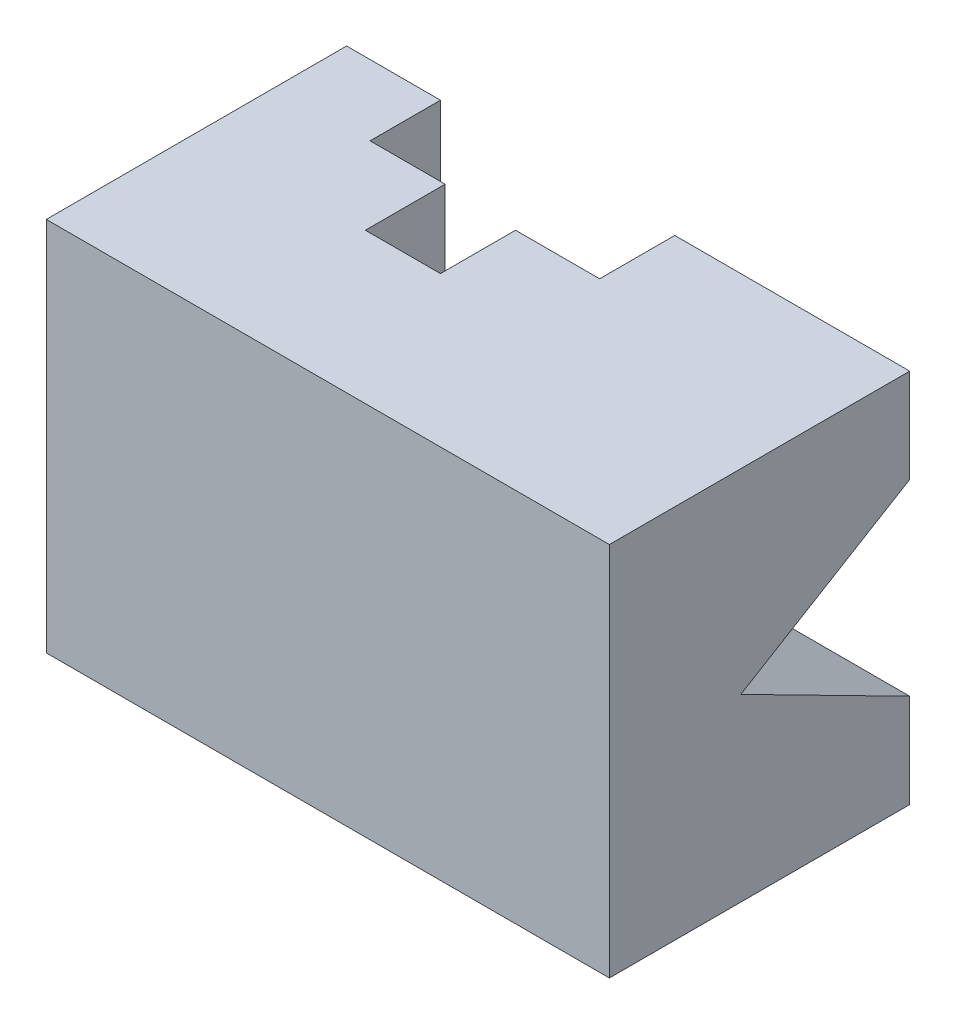
SolidWorks part; units mm, degrees
ref_plane "Front Plane" through (0, 0, 0) normal (0, 0, 1) x (1, 0, 0)
ref_plane "Top Plane" through (0, 0, 0) normal (0, 1, 0) x (1, 0, 0)
ref_plane "Right Plane" through (0, 0, 0) normal (1, 0, 0) x (0, 0, -1)
sketch "Sketch1" plane through (0, 0, 0) normal (0, 1, 0) x (1, 0, 0)
  line L0 (-105.5769, -23.6058) -> (44.4231, -23.6058)
  line L1 (44.4231, -23.6058) -> (44.4231, 56.3942)
  line L2 (44.4231, 56.3942) -> (-18.1731, 56.3942)
  line L3 (-18.1731, 56.3942) -> (-18.1731, 36.3942)
  line L4 (-18.1731, 36.3942) -> (-40.5769, 36.3942)
  line L5 (-40.5769, 36.3942) -> (-40.5769, 16.3942)
  line L6 (-40.5769, 16.3942) -> (-60.5769, 16.3942)
  line L7 (-60.5769, 16.3942) -> (-60.5769, 37.6442)
  line L8 (-60.5769, 37.6442) -> (-80.5769, 37.6442)
  line L9 (-80.5769, 37.6442) -> (-80.5769, 56.3942)
  line L10 (-80.5769, 56.3942) -> (-105.5769, 56.3942)
  line L11 (-105.5769, 56.3942) -> (-105.5769, -23.6058)
  dimension "D1" = 150
  dimension "D2" = 80
  dimension "D3" = 80
  dimension "D4" = 25
  dimension "D5" = 20
  dimension "D6" = 20
extrude "Boss-Extrude1" add sketch "Sketch1" against normal blind 100
sketch "Sketch3" plane through (44.4231, 0, 0) normal (1, 0, 0) x (0, 0, -1)
  line L1 (56.3942, -100) -> (56.3942, 0) construction
  line L4 (56.3942, -25) -> (11.3942, -52.0737)
  line L5 (56.3942, -75) -> (11.3942, -52.0737)
  line L6 (56.3942, -25) -> (56.3942, -75)
extrude "Cut-Extrude1" cut sketch "Sketch3" against normal blind 50
